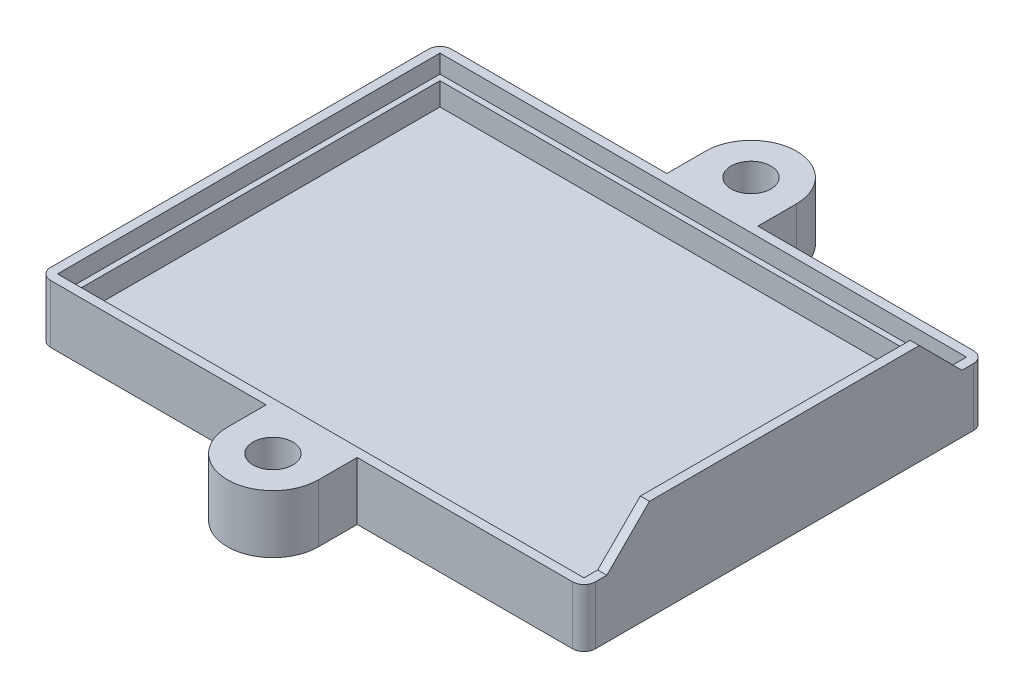
SolidWorks part; units mm, degrees
ref_plane "Front Plane" through (0, 0, 0) normal (0, 0, 1) x (1, 0, 0)
ref_plane "Top Plane" through (0, 0, 0) normal (0, 1, 0) x (1, 0, 0)
ref_plane "Right Plane" through (0, 0, 0) normal (1, 0, 0) x (0, 0, -1)
sketch "Sketch1" plane through (0, 0, 0) normal (0, 1, 0) x (1, 0, 0)
  line L1 (23.925, 17.6) -> (-23.925, 17.6)
  line L2 (23.925, 17.6) -> (23.925, -17.6)
  line L3 (23.925, -17.6) -> (-23.925, -17.6)
  line L4 (-23.925, 17.6) -> (-23.925, -17.6)
  line L5 (23.925, 17.6) -> (-23.925, -17.6) construction
  line L6 (23.925, -17.6) -> (-23.925, 17.6) construction
  point P0 (0, 0)
  dimension "D1" = 47.85
  dimension "D2" = 35.2
extrude "Boss-Extrude1" add sketch "Sketch1" along normal blind 5.1
sketch "Sketch2" plane through (0, 5.1, 0) normal (0, 1, 0) x (1, 0, 0)
  line L0 (-23.125, 16.8) -> (-23.925, 16.8) construction
  line L1 (23.125, -16.8) -> (-23.125, -16.8)
  line L2 (23.125, -16.8) -> (23.125, 16.8)
  line L3 (23.125, 16.8) -> (-23.125, 16.8)
  line L4 (-23.125, -16.8) -> (-23.125, 16.8)
  line L5 (23.125, -16.8) -> (-23.125, 16.8) construction
  line L6 (23.125, 16.8) -> (-23.125, -16.8) construction
  line L7 (-23.925, 17.6) -> (-23.925, -17.6) construction
  line L8 (-23.125, 16.8) -> (-23.125, 17.6) construction
  line L9 (23.925, 17.6) -> (-23.925, 17.6) construction
  point P0 (0, 0)
  dimension "D1" = 0.8
extrude "Cut-Extrude1" cut sketch "Sketch2" against normal blind 1.6
sketch "Sketch3" plane through (0, 3.5, 0) normal (0, 1, 0) x (1, 0, 0)
  line L8 (-22.625, 16.3) -> (-22.625, -16.3)
  line L9 (-22.625, -16.3) -> (22.625, -16.3)
  line L10 (22.625, -16.3) -> (22.625, 16.3)
  line L11 (22.625, 16.3) -> (-22.625, 16.3)
  line L12 (-22.625, 16.3) -> (-22.625, -16.3)
  line L13 (-22.625, -16.3) -> (22.625, -16.3)
  line L14 (22.625, -16.3) -> (22.625, 16.3)
  line L15 (22.625, 16.3) -> (-22.625, 16.3)
  dimension "D1" = 0.5
extrude "Cut-Extrude2" cut sketch "Sketch3" against normal offset from surface (2 mm away) 1.5 up to face at (0, 0, 0)
sketch "Sketch4" plane through (23.925, 0, 0) normal (1, 0, 0) x (0, 0, -1)
  line L0 (-15.6, 5.1) -> (-11.85, 8.85)
  line L1 (-17.6, 5.1) -> (17.6, 5.1) construction
  line L2 (-11.85, 8.85) -> (11.85, 8.85)
  line L3 (0, 12.7608) -> (0, -5.0154) construction
  line L4 (15.6, 5.1) -> (11.85, 8.85)
  line L5 (-17.6, 5.1) -> (-17.6, 0) construction
  line L6 (-15.6, 5.1) -> (15.6, 5.1)
  dimension "D1" = 2
  dimension "D2" = 3.75
  dimension "D3" = 45
extrude "Boss-Extrude2" add sketch "Sketch4" against normal up to surface (0.8 mm away) up to face at (23.125, 4.3, 0)
fillet "Fillet1" radius 1 4 edges at (-23.925, 2.55, -17.6) (23.925, 2.55, -17.6) (-23.925, 2.55, 17.6) (23.925, 2.55, 17.6)
sketch "Sketch6" plane through (0, 0, 0) normal (0, -1, 0) x (1, 0, 0)
  line L0 (0, 25.4509) -> (0, -24.5268) construction
  line L3 (-31.6849, 0) -> (31.1194, 0) construction
  line L5 (-22.925, 17.6) -> (22.925, 17.6) construction
  line L6 (-4, 21) -> (-4, 17.6)
  line L7 (4, 21) -> (4, 17.6)
  line L8 (4, -21) -> (4, -17.6)
  line L9 (-4, -21) -> (-4, -17.6)
  circle A1 centre (0, 21) radius 4
  circle A2 centre (0, 21) radius 1.75
  circle A3 centre (0, -21) radius 1.75
  circle A4 centre (0, -21) radius 4
  point P5 (0, 0)
  line M13 (-22.925, -17.6) -> (22.925, -17.6)
  line M17 (22.925, 17.6) -> (-22.925, 17.6)
  dimension "D1" = 42
  dimension "D2" = 8
  dimension "D3" = 3.5
extrude "Boss-Extrude3" add sketch "Sketch6" against normal up to surface (5.1 mm away) contours A1 L6 M17 | A1 A2 M17 | A1 L7 M17 | L9 A4 M13 | A4 A3 M13 | A4 L8 M13
